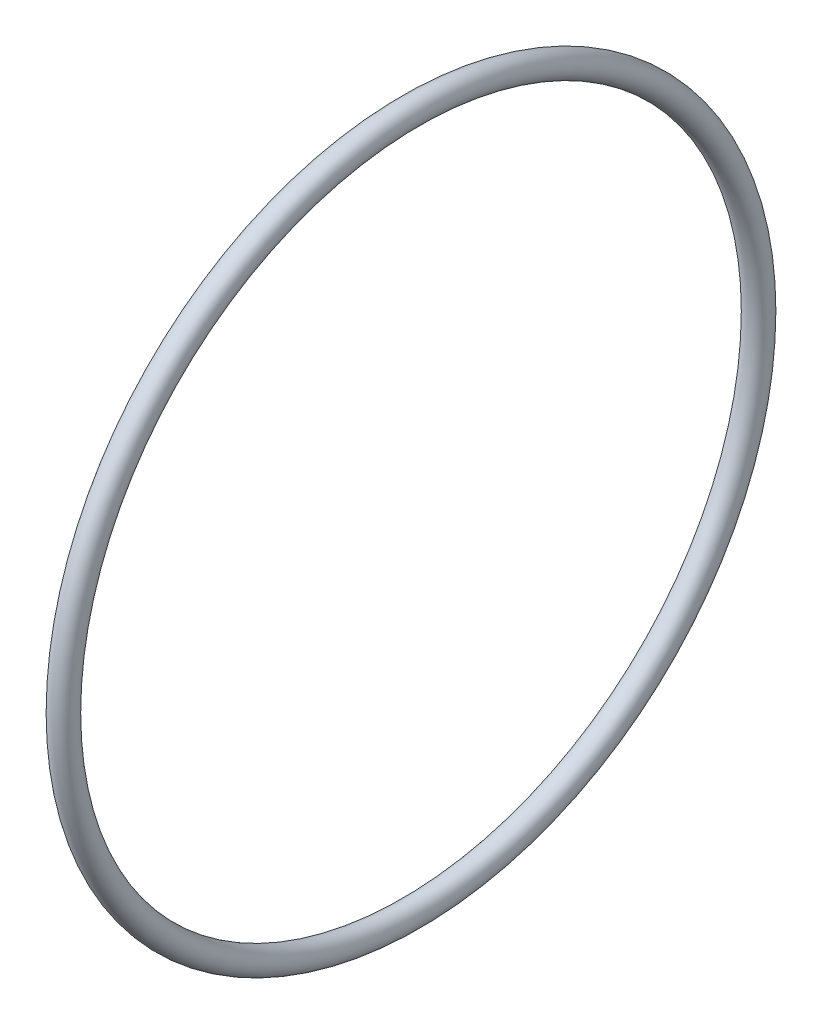
SolidWorks part; units mm, degrees
material "未指定"
ref_plane "正面" through (0, 0, 0) normal (0, 0, 1) x (1, 0, 0)
ref_plane "平面" through (0, 0, 0) normal (0, 1, 0) x (1, 0, 0)
ref_plane "右側面" through (0, 0, 0) normal (1, 0, 0) x (0, 0, -1)
sketch "ｽｹｯﾁ1" plane through (0, 0, 0) normal (0, 0, 1) x (1, 0, 0)
  line L0 (0, 0) -> (10, 0) construction
  circle A0 centre (0, 44.05) radius 1.55
  dimension "D2" = 3.1
  dimension "D1" = 44.05
revolve "Oリング" add sketch "ｽｹｯﾁ1" angle 360 about L0
equation "\"FACE_GROOVE_ID\" = 85"
equation "\"ORING_W\" = 3.1"
equation "\"D1@ｽｹｯﾁ1\" = (\"FACE_GROOVE_ID\" + \"ORING_W\") / 2"
equation "\"D2@ｽｹｯﾁ1\" = \"ORING_W\""
